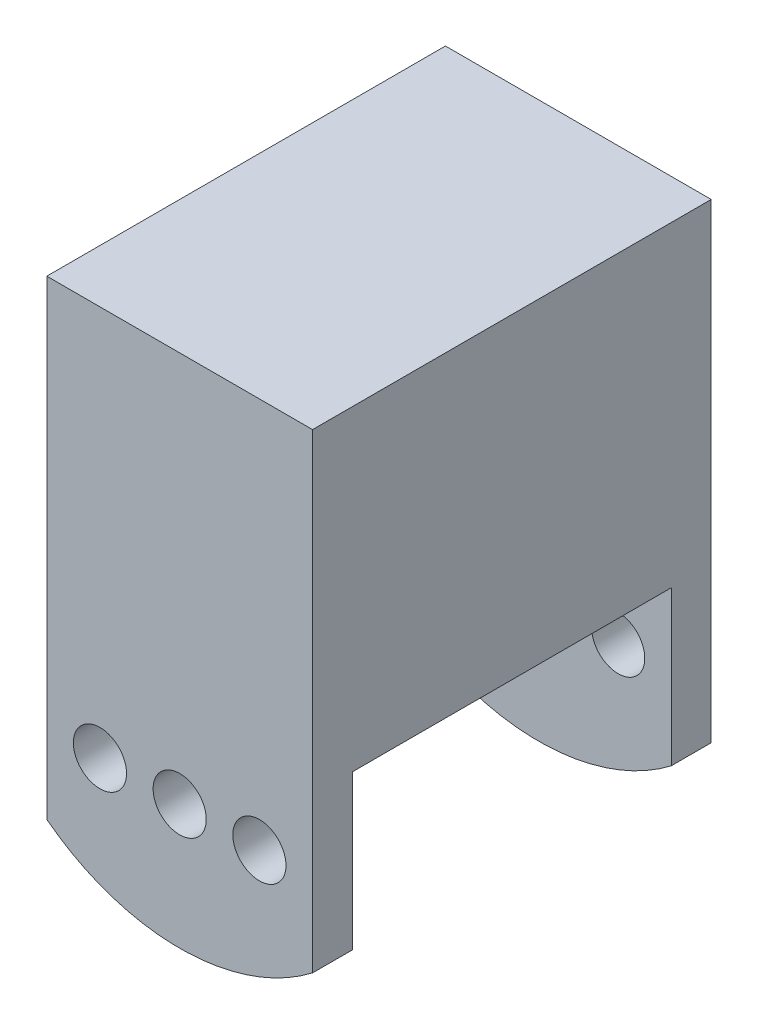
SolidWorks part; units mm, degrees
ref_plane "Front Plane" through (0, 0, 0) normal (0, 0, 1) x (1, 0, 0)
ref_plane "Top Plane" through (0, 0, 0) normal (0, 1, 0) x (1, 0, 0)
ref_plane "Right Plane" through (0, 0, 0) normal (1, 0, 0) x (0, 0, -1)
sketch "Sketch1" plane through (0, 0, 0) normal (0, 0, 1) x (1, 0, 0)
  line L0 (0, 0) -> (-10, -13.0323) construction
  line L1 (0, 0) -> (10, -13.0323) construction
  line L2 (-10, -13.0323) -> (10, -13.0323) construction
  line L9 (-10, 22.3777) -> (10, 22.3777)
  line L10 (-10, -13.0323) -> (-10, 22.3777)
  line L11 (10, 22.3777) -> (10, -13.0323)
  arc A0 (-10, -13.0323) -> (10, -13.0323) centre (0, 0) ccw
  circle A2 centre (0, -7.0323) radius 2
  circle A3 centre (6, -7.0323) radius 2
  circle A4 centre (-6, -7.0323) radius 2
  dimension "D6" = 4
  dimension "D7" = 4
  dimension "D10" = 4
  dimension "D1" = 75
  dimension "D2" = 20
  dimension "D3" = 35.41
  dimension "D5" = 6
  dimension "D8" = 6
  dimension "D9" = 6
extrude "Boss-Extrude1" add sketch "Sketch1" along normal blind 30
sketch "Sketch2" plane through (10, 0, 0) normal (1, 0, 0) x (0, 0, -1)
  line L0 (-30, -16.4268) -> (0, -16.4268) construction
  line L1 (-27, -16.4268) -> (-3, -16.4268)
  line L2 (-27, -16.4268) -> (-27, -1.4268)
  line L3 (-27, -1.4268) -> (-3, -1.4268)
  line L4 (-3, -16.4268) -> (-3, -1.4268)
  line L5 (-30, -13.0323) -> (-30, -16.4268) construction
  line L6 (0, -16.4268) -> (0, -13.0323) construction
  line L7 (-30, -13.0323) -> (0, -13.0323) construction
  dimension "D1" = 3
  dimension "D2" = 3
  dimension "D3" = 11.6055
extrude "Cut-Extrude1" cut sketch "Sketch2" against normal through all
sketch "Sketch3" plane through (-10, 0, 0) normal (-1, 0, 0) x (0, 0, 1)
  line L0 (3, -1.4268) -> (27, -1.4268) construction
  circle A0 centre (15, 10.4732) radius 8.9
  circle A1 centre (15, 10.4732) radius 6 construction
  circle A2 centre (15, 16.4732) radius 2
  circle A3 centre (15, 4.4732) radius 2
  circle A4 centre (9, 10.4732) radius 2
  circle A5 centre (21, 10.4732) radius 2
  point P5 (15, -1.4268)
  dimension "D1" = 17.8
  dimension "D2" = 11.9
  dimension "D3" = 12
  dimension "D4" = 4
  dimension "D5" = 4
  dimension "D6" = 4
  dimension "D7" = 4
extrude "Cut-Extrude2" cut sketch "Sketch3" against normal blind 3
